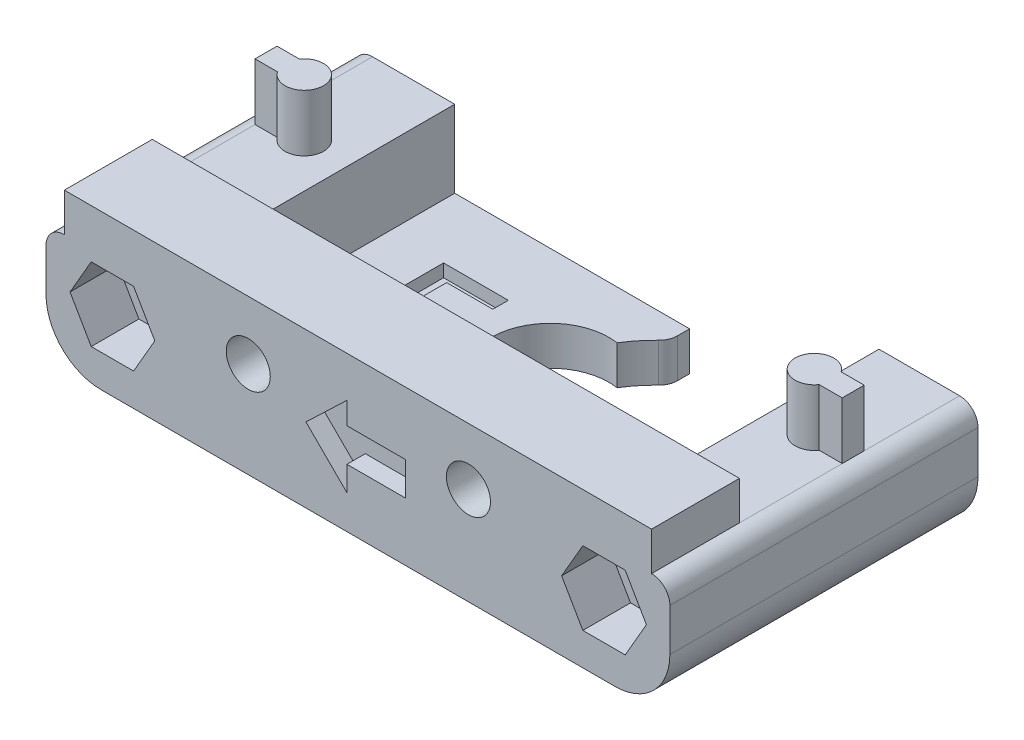
SolidWorks part; units mm, degrees
ref_plane "正面" through (0, 0, 0) normal (0, 0, 1) x (1, 0, 0)
ref_plane "平面" through (0, 0, 0) normal (0, 1, 0) x (1, 0, 0)
ref_plane "右側面" through (0, 0, 0) normal (1, 0, 0) x (0, 0, -1)
ref_plane "平面1" through (0, -24, 0) normal (0, -1, 0) x (1, 0, 0)
sketch "ｽｹｯﾁ1" plane through (0, -24, 0) normal (0, -1, 0) x (1, 0, 0)
  line L0 (-17, 4.6) -> (-17, -10.9074)
  line L1 (-17, -10.9074) -> (1.2842, -10.9074)
  line L2 (1.2842, -10.9074) -> (1.2842, -9.0365)
  line L3 (9.2842, -10.9074) -> (17, -10.9074)
  line L4 (17, -10.9074) -> (17, 4.6)
  line L5 (17, 4.6) -> (-17, 4.6)
  arc A0 (1.2842, -9.0365) -> (-0.0316, -3.2276) centre (-0.5158, -6.3907) cw
  arc A1 (-0.0316, -3.2276) -> (9.2842, -10.9074) centre (5.1842, -6.3907) cw
extrude "ﾎﾞｽ - 押し出し1" add sketch "ｽｹｯﾁ1" against normal blind 2.1212
sketch "ｽｹｯﾁ2" plane through (0, 0, -10.9074) normal (0, 0, -1) x (-1, 0, 0)
  line L0 (17, -21.8788) -> (17, -24)
  line L1 (17, -24) -> (-1.2842, -24)
  line L2 (-1.2842, -24) -> (-1.2842, -21.8788)
  line L3 (-1.2842, -21.8788) -> (17, -21.8788)
extrude "ﾎﾞｽ - 押し出し2" add sketch "ｽｹｯﾁ2" along normal blind 1.2836
sketch "ｽｹｯﾁ3" plane through (0, 0, -10.9074) normal (0, 0, -1) x (-1, 0, 0)
  line L0 (-9.2842, -21.8788) -> (-9.2842, -24)
  line L1 (-9.2842, -24) -> (-17, -24)
  line L2 (-17, -24) -> (-17, -21.8788)
  line L3 (-17, -21.8788) -> (-9.2842, -21.8788)
extrude "ﾎﾞｽ - 押し出し3" add sketch "ｽｹｯﾁ3" along normal blind 1.2836
sketch "ｽｹｯﾁ4" plane through (0, -21.8788, 0) normal (0, 1, 0) x (-1, 0, 0)
  line L0 (17, 4.6) -> (17, -12.191)
  line L1 (17, -12.191) -> (11.5158, -12.191)
  line L2 (11.5158, -12.191) -> (11.5158, -0.1907)
  line L3 (11.5158, -0.1907) -> (-9.2842, -0.1907)
  line L4 (-9.2842, -0.1907) -> (-9.2842, -12.191)
  line L5 (-11.6042, -12.191) -> (-17, -12.191)
  line L6 (-17, -12.191) -> (-17, 4.6)
  line L7 (-17, 4.6) -> (17, 4.6)
  spline S0 degree 3 poles (-9.2842, -12.191) (-10.0575, -12.191) (-10.8308, -12.191) (-11.6042, -12.191) knots 0 0 0 0 1 1 1 1
extrude "ﾎﾞｽ - 押し出し4" add sketch "ｽｹｯﾁ4" along normal blind 4.2
sketch "ｽｹｯﾁ5" plane through (0, -17.6788, 0) normal (0, 1, 0) x (-1, 0, 0)
  line L0 (-15.9998, -0.1907) -> (-15.9998, 4.6)
  line L1 (-15.9998, 4.6) -> (15.9995, 4.6)
  line L2 (15.9995, 4.6) -> (15.9995, -0.1907)
  line L3 (15.9995, -0.1907) -> (-15.9998, -0.1907)
extrude "ﾎﾞｽ - 押し出し5" add sketch "ｽｹｯﾁ5" along normal blind 2.1
sketch "ｽｹｯﾁ6" plane through (9.2842, 0, 0) normal (-1, 0, 0) x (0, 0, 1)
  line L0 (-12.191, -17.6788) -> (-12.191, -21.8788)
  line L1 (-12.191, -21.8788) -> (-0.1907, -21.8788)
  line L2 (-0.1907, -21.8788) -> (-0.1907, -17.6788)
  line L3 (-0.1907, -17.6788) -> (-12.191, -17.6788)
extrude "ｶｯﾄ - 押し出し1" cut sketch "ｽｹｯﾁ6" against normal blind 2.32
sketch "ｽｹｯﾁ7" plane through (0, -24, 0) normal (0, -1, 0) x (1, 0, 0)
  line L0 (1.2842, -11.0812) -> (1.2842, -9.0365)
  arc A0 (1.2842, -9.0365) -> (-0.0316, -9.5539) centre (-0.5158, -6.3907) cw
  arc A1 (-0.0316, -9.5539) -> (1.2842, -11.0812) centre (5.1842, -6.3907) ccw
extrude "ｶｯﾄ - 押し出し2" cut sketch "ｽｹｯﾁ7" against normal through all
sketch "ｽｹｯﾁ8" plane through (0, -17.6788, 0) normal (0, 1, 0) x (-1, 0, 0)
  line L0 (15.9995, -6.9907) -> (14.7775, -6.9907)
  line L1 (14.7775, -5.7907) -> (15.9995, -5.7907)
  line L2 (15.9995, -5.7907) -> (15.9995, -6.9907)
  arc A0 (14.7775, -6.9907) -> (14.7775, -5.7907) centre (13.9158, -6.3907) cw
extrude "ﾎﾞｽ - 押し出し6" add sketch "ｽｹｯﾁ8" along normal blind 3.1
sketch "ｽｹｯﾁ9" plane through (0, -17.6788, 0) normal (0, 1, 0) x (-1, 0, 0)
  line L0 (-15.9998, -5.7907) -> (-14.7458, -5.7907)
  line L1 (-14.7458, -6.9907) -> (-15.9998, -6.9907)
  line L2 (-15.9998, -6.9907) -> (-15.9998, -5.7907)
  arc A0 (-14.7458, -5.7907) -> (-14.7458, -6.9907) centre (-13.8842, -6.3907) cw
extrude "ﾎﾞｽ - 押し出し7" add sketch "ｽｹｯﾁ9" along normal blind 3.1
sketch "ｽｹｯﾁ10" plane through (0, 0, 4.6) normal (0, 0, 1) x (1, 0, 0)
  line L0 (-0.6, -17.8) -> (-2.8347, -19.9353)
  line L1 (-2.8347, -19.9353) -> (-0.6, -22.1599)
  line L2 (-0.6, -22.1599) -> (-0.6, -20.8182)
  line L3 (-0.6, -20.8182) -> (2.5893, -20.8182)
  line L4 (2.5893, -20.8182) -> (2.5893, -19)
  line L5 (2.5893, -19) -> (-0.6, -19)
  line L6 (-0.6, -19) -> (-0.6, -17.8)
extrude "ｶｯﾄ - 押し出し3" cut sketch "ｽｹｯﾁ10" against normal blind 1
sketch "ｽｹｯﾁ11" plane through (0, 0, 4.6) normal (0, 0, 1) x (1, 0, 0)
  line L0 (-14.5358, -22.2306) -> (-12.2264, -22.2306)
  line L1 (-12.2264, -22.2306) -> (-11.0717, -20.2306)
  line L2 (-11.0717, -20.2306) -> (-12.2264, -18.2306)
  line L3 (-12.2264, -18.2306) -> (-14.5358, -18.2306)
  line L4 (-14.5358, -18.2306) -> (-15.6905, -20.2306)
  line L5 (-15.6905, -20.2306) -> (-14.5358, -22.2306)
extrude "ｶｯﾄ - 押し出し4" cut sketch "ｽｹｯﾁ11" against normal blind 2.6
sketch "ｽｹｯﾁ12" plane through (0, 0, 4.6) normal (0, 0, 1) x (1, 0, 0)
  line L0 (12.255, -22.232) -> (14.5644, -22.232)
  line L1 (14.5644, -22.232) -> (15.7191, -20.232)
  line L2 (15.7191, -20.232) -> (14.5644, -18.232)
  line L3 (14.5644, -18.232) -> (12.255, -18.232)
  line L4 (12.255, -18.232) -> (11.1003, -20.232)
  line L5 (11.1003, -20.232) -> (12.255, -22.232)
extrude "ｶｯﾄ - 押し出し5" cut sketch "ｽｹｯﾁ12" against normal blind 2.6
sketch "ｽｹｯﾁ13" plane through (0, -21.8788, 0) normal (0, 1, 0) x (-1, 0, 0)
  line L0 (7.519, -7.7525) -> (5.0034, -7.7525)
  line L1 (5.0034, -7.7525) -> (5.0034, -8.5967)
  line L2 (5.0034, -8.5967) -> (8.5307, -8.5967)
  line L3 (8.5307, -8.5967) -> (8.5307, -3.627)
  line L4 (8.5307, -3.627) -> (7.519, -3.627)
  line L5 (7.519, -3.627) -> (7.519, -7.7525)
extrude "ｶｯﾄ - 押し出し6" cut sketch "ｽｹｯﾁ13" against normal blind 0.7
sketch "ｽｹｯﾁ14" plane through (0, 0, -0.1907) normal (0, 0, -1) x (-1, 0, 0)
  line L0 (-7.1858, -20.684) -> (-4.8764, -20.684)
  line L1 (-4.8764, -20.684) -> (-3.7217, -18.684)
  line L2 (-3.7217, -18.684) -> (-4.8764, -16.684)
  line L3 (-4.8764, -16.684) -> (-7.1858, -16.684)
  line L4 (-7.1858, -16.684) -> (-8.3405, -18.684)
  line L5 (-8.3405, -18.684) -> (-7.1858, -20.684)
extrude "ｶｯﾄ - 押し出し7" cut sketch "ｽｹｯﾁ14" against normal blind 3.0907
sketch "ｽｹｯﾁ15" plane through (0, 0, -0.1907) normal (0, 0, -1) x (-1, 0, 0)
  line L0 (4.8359, -20.764) -> (7.1453, -20.764)
  line L1 (7.1453, -20.764) -> (8.3, -18.764)
  line L2 (8.3, -18.764) -> (7.1453, -16.764)
  line L3 (7.1453, -16.764) -> (4.8359, -16.764)
  line L4 (4.8359, -16.764) -> (3.6812, -18.764)
  line L5 (3.6812, -18.764) -> (4.8359, -20.764)
extrude "ｶｯﾄ - 押し出し8" cut sketch "ｽｹｯﾁ15" against normal blind 3.0907
hole_wizard "穴1" positions "ｽｹｯﾁ17" profile "ｽｹｯﾁ16" legacy
sketch "ｽｹｯﾁ17" plane through (0, 0, 4.6) normal (0, 0, 1) x (1, 0, 0)
  point P0 (-5.9777, -18.7708)
sketch "ｽｹｯﾁ16" plane through (-5.9777, -18.7708, 4.6) normal (1, 0, 0) x (0, -1, 0)
  line L0 (0, 0) -> (0, 16.7911)
  line L1 (0, 16.7911) -> (1.2, 16.7911)
  line L2 (1.2, 16.7911) -> (1.2, 0)
  line L3 (1.2, 0) -> (0, 0)
  line L4 (0, 110) -> (0, -10) construction
  dimension "直径" = 2.4
  dimension "深さ" = 16.791
hole_wizard "穴2" positions "ｽｹｯﾁ19" profile "ｽｹｯﾁ18" legacy
sketch "ｽｹｯﾁ19" plane through (0, 0, 4.6) normal (0, 0, 1) x (1, 0, 0)
  point P0 (6.022, -18.6869)
sketch "ｽｹｯﾁ18" plane through (6.022, -18.6869, 4.6) normal (1, 0, 0) x (0, -1, 0)
  line L0 (0, 0) -> (0, 16.7911)
  line L1 (0, 16.7911) -> (1.2, 16.7911)
  line L2 (1.2, 16.7911) -> (1.2, 0)
  line L3 (1.2, 0) -> (0, 0)
  line L4 (0, 110) -> (0, -10) construction
  dimension "直径" = 2.4
  dimension "深さ" = 16.791
hole_wizard "穴3" positions "ｽｹｯﾁ21" profile "ｽｹｯﾁ20" legacy
sketch "ｽｹｯﾁ21" plane through (0, 0, -12.191) normal (0, 0, -1) x (-1, 0, 0)
  point P0 (-13.4, -20.25)
sketch "ｽｹｯﾁ20" plane through (13.4, -20.25, -12.191) normal (1, 0, 0) x (0, 1, 0)
  line L0 (0, 0) -> (0, 16.7911)
  line L1 (0, 16.7911) -> (1.2, 16.7911)
  line L2 (1.2, 16.7911) -> (1.2, 0)
  line L3 (1.2, 0) -> (0, 0)
  line L4 (0, 110) -> (0, -10) construction
  dimension "直径" = 2.4
  dimension "深さ" = 16.7911
hole_wizard "穴4" positions "ｽｹｯﾁ23" profile "ｽｹｯﾁ22" legacy
sketch "ｽｹｯﾁ23" plane through (0, 0, -12.191) normal (0, 0, -1) x (-1, 0, 0)
  point P0 (13.4, -20.25)
sketch "ｽｹｯﾁ22" plane through (-13.4, -20.25, -12.191) normal (1, 0, 0) x (0, 1, 0)
  line L0 (0, 0) -> (0, 16.7911)
  line L1 (0, 16.7911) -> (1.2, 16.7911)
  line L2 (1.2, 16.7911) -> (1.2, 0)
  line L3 (1.2, 0) -> (0, 0)
  line L4 (0, 110) -> (0, -10) construction
  dimension "直径" = 2.4
  dimension "深さ" = 16.7911
fillet "ﾌｨﾚｯﾄ1" radius 1 1 edges
fillet "ﾌｨﾚｯﾄ2" radius 1 1 edges at (1.2842, -22.9394, -11.0812)
fillet "ﾌｨﾚｯﾄ3" radius 1 1 edges at (-17, -17.6788, -3.7955)
fillet "ﾌｨﾚｯﾄ4" radius 1 1 edges at (17, -17.6788, -3.7955)
fillet "ﾌｨﾚｯﾄ5" radius 3 1 edges at (-17, -24, -3.7955)
fillet "ﾌｨﾚｯﾄ6" radius 3 1 edges at (17, -24, -3.7955)
